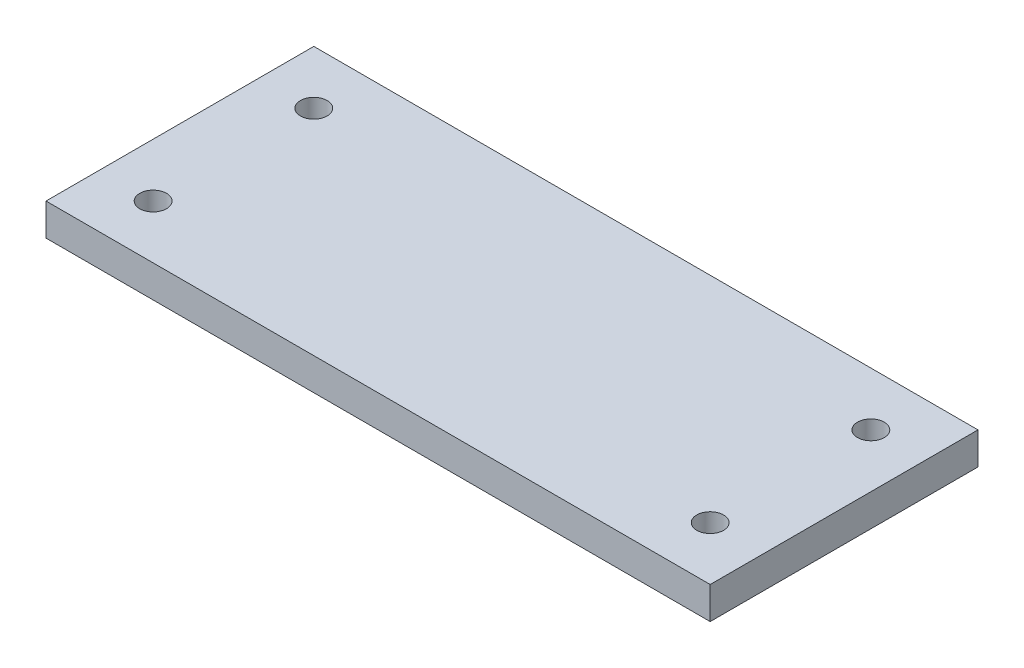
SolidWorks part; units mm, degrees
ref_plane "Płaszczyzna przednia" through (0, 0, 0) normal (0, 0, 1) x (1, 0, 0)
ref_plane "Płaszczyzna górna" through (0, 0, 0) normal (0, 1, 0) x (1, 0, 0)
ref_plane "Płaszczyzna prawa" through (0, 0, 0) normal (1, 0, 0) x (0, 0, -1)
sketch "Szkic1" plane through (0, 0, 0) normal (0, 1, 0) x (1, 0, 0)
  line L1 (0, 0) -> (62, 0)
  line L2 (0, 0) -> (0, 25)
  line L3 (0, 25) -> (62, 25)
  line L4 (62, 0) -> (62, 25)
  dimension "D1" = 62
  dimension "D2" = 25
extrude "Dodanie-wyciągnięcie1" add sketch "Szkic1" along normal blind 3
sketch "Szkic2" plane through (0, 3, 0) normal (0, 1, 0) x (1, 0, 0)
  line L0 (0, 25) -> (0, 0) construction
  line L1 (62, 25) -> (0, 25) construction
  line L2 (0, 0) -> (62, 0) construction
  line L3 (62, 0) -> (62, 25) construction
  circle A0 centre (5, 5) radius 1.25
  circle A1 centre (57, 5) radius 1.25
  circle A2 centre (57, 20) radius 1.25
  circle A3 centre (5, 20) radius 1.25
  dimension "D1" = 2.5
  dimension "D2" = 2.5
  dimension "D3" = 2.5
  dimension "D4" = 2.5
  dimension "D7" = 5
  dimension "D11" = 5
  dimension "D5" = 5
  dimension "D6" = 5
  dimension "D8" = 5
  dimension "D9" = 5
  dimension "D10" = 5
  dimension "D13" = 5
extrude "Wytnij-wyciągnięcie1" cut sketch "Szkic2" against normal blind 5
